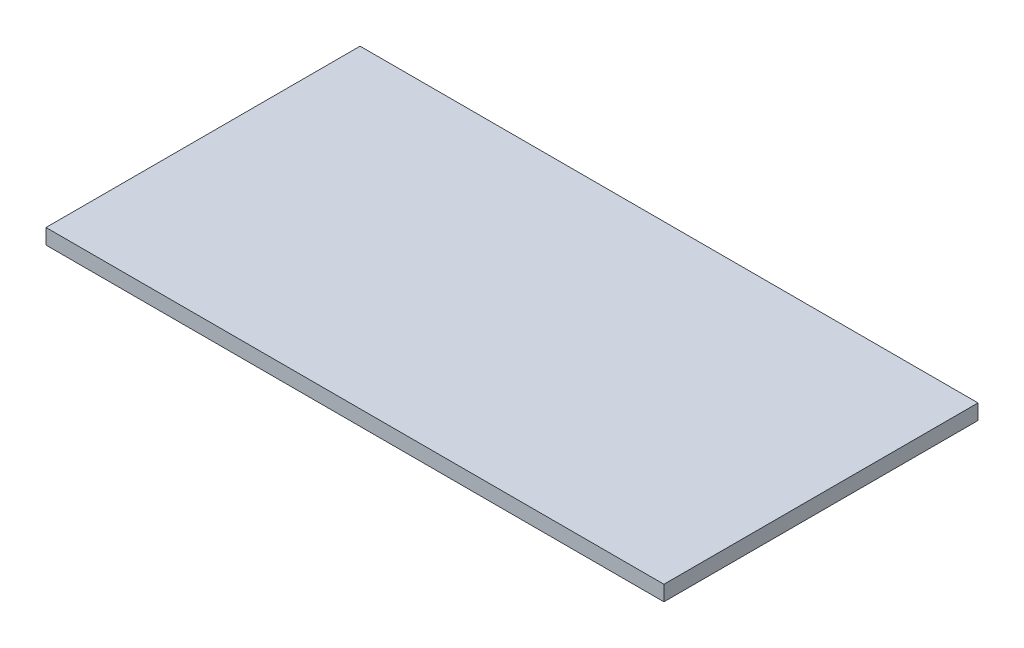
SolidWorks part; units mm, degrees
ref_plane "Front Plane" through (0, 0, 0) normal (0, 0, 1) x (1, 0, 0)
ref_plane "Top Plane" through (0, 0, 0) normal (0, 1, 0) x (1, 0, 0)
ref_plane "Right Plane" through (0, 0, 0) normal (1, 0, 0) x (0, 0, -1)
sketch "Sketch1" plane through (0, 0, 0) normal (0, 1, 0) x (1, 0, 0)
  line L5 (0, 0) -> (205.8, 0)
  line L6 (0, 0) -> (0, 104.6)
  line L7 (0, 104.6) -> (205.8, 104.6)
  line L8 (205.8, 0) -> (205.8, 104.6)
  dimension "D1" = 205.8
  dimension "D2" = 104.6
extrude "Boss-Extrude1" add sketch "Sketch1" along normal blind 5.08 contours L6 L5 L8 L7
